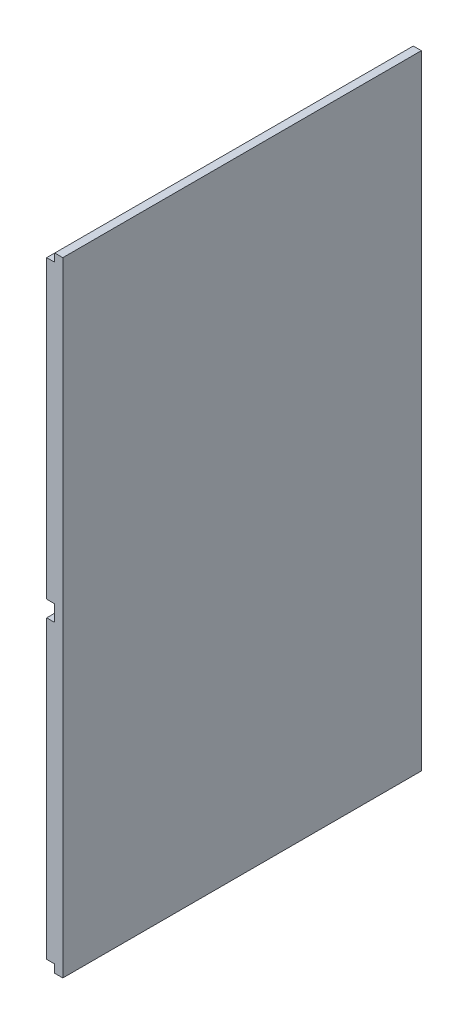
SolidWorks part; units mm, degrees
ref_plane "Front" through (0, 0, 0) normal (0, 0, 1) x (1, 0, 0)
ref_plane "Top" through (0, 0, 0) normal (0, 1, 0) x (1, 0, 0)
ref_plane "Right" through (0, 0, 0) normal (1, 0, 0) x (0, 0, -1)
sketch "Sketch1" plane through (0, 0, 0) normal (1, 0, 0) x (0, 0, -1)
  line L1 (-200, -348) -> (200, -348)
  line L2 (-200, -348) -> (-200, 348)
  line L3 (-200, 348) -> (200, 348)
  line L4 (200, -348) -> (200, 348)
  line L5 (-200, -348) -> (200, 348) construction
  line L6 (-200, 348) -> (200, -348) construction
  point P0 (0, 0)
  dimension "D1" = 400
  dimension "D2" = 696
extrude "Boss-Extrude1" add sketch "Sketch1" along normal blind 18
sketch "Sketch2" plane through (0, 0, 0) normal (-1, 0, 0) x (0, 0, 1)
  line L0 (200, 348) -> (200, -348) construction
  line L1 (-200, -348) -> (200, -348)
  line L2 (-200, -348) -> (-200, -339)
  line L3 (-200, -339) -> (200, -339)
  line L4 (200, -348) -> (200, -339)
  line L5 (-200, -348) -> (-200, 348) construction
  line L6 (200, 348) -> (-200, 348)
  line L7 (200, 348) -> (200, 339)
  line L8 (200, 339) -> (-200, 339)
  line L9 (-200, 348) -> (-200, 339)
  dimension "D1" = 9
  dimension "D2" = 9
extrude "Cut-Extrude1" cut sketch "Sketch2" against normal blind 9
sketch "Sketch3" plane through (0, 0, 0) normal (-1, 0, 0) x (0, 0, 1)
  line L0 (200, 339) -> (200, -339) construction
  line L1 (-200, -9) -> (200, -9)
  line L2 (-200, -9) -> (-200, 9)
  line L3 (-200, 9) -> (200, 9)
  line L4 (200, -9) -> (200, 9)
  line L5 (-200, -9) -> (200, 9) construction
  line L6 (-200, 9) -> (200, -9) construction
  point P0 (0, 0)
  dimension "D1" = 18
extrude "Cut-Extrude2" cut sketch "Sketch3" against normal blind 9
